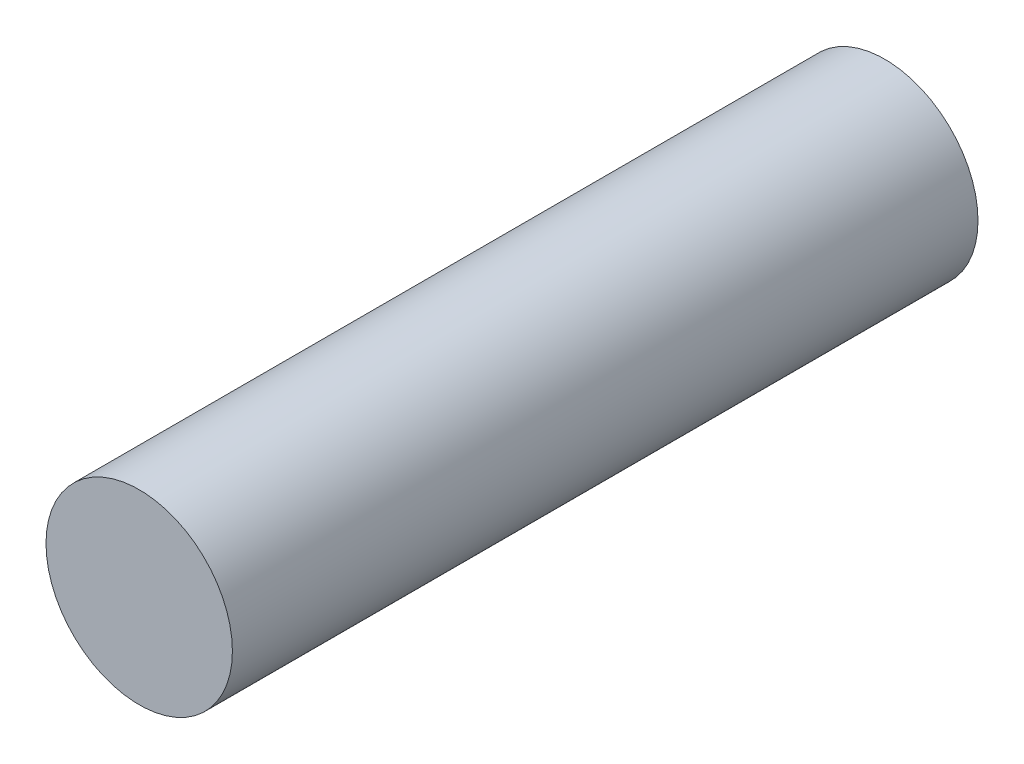
SolidWorks part; units mm, degrees
ref_plane "Front Plane" through (0, 0, 0) normal (0, 0, 1) x (1, 0, 0)
ref_plane "Top Plane" through (0, 0, 0) normal (0, 1, 0) x (1, 0, 0)
ref_plane "Right Plane" through (0, 0, 0) normal (1, 0, 0) x (0, 0, -1)
sketch "Sketch1" plane through (0, 0, 0) normal (0, 0, 1) x (1, 0, 0)
  circle A0 centre (0, 0) radius 3.175
  dimension "D1" = 6.35
extrude "Boss-Extrude1" add sketch "Sketch1" against normal blind 25.4
